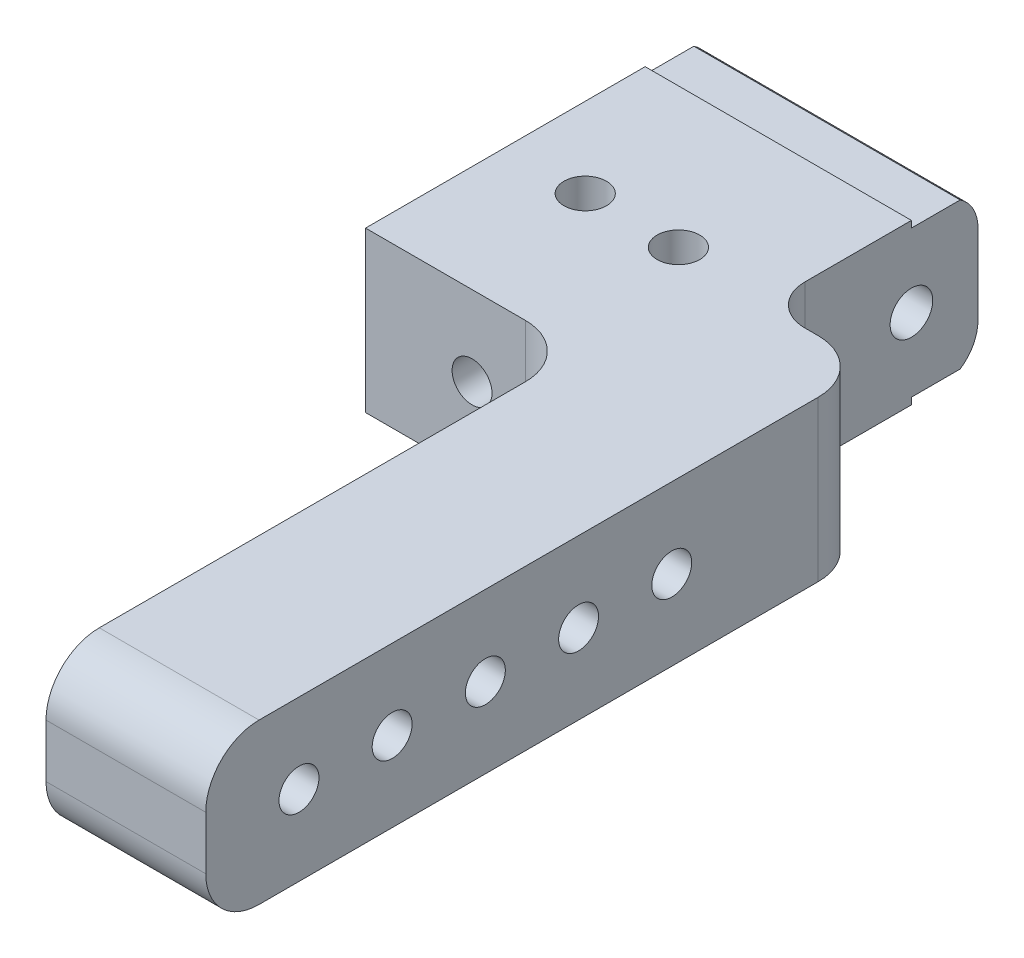
SolidWorks part; units mm, degrees
ref_plane "Front" through (0, 0, 0) normal (0, 0, 1) x (1, 0, 0)
ref_plane "Top" through (0, 0, 0) normal (0, 1, 0) x (1, 0, 0)
ref_plane "Right" through (0, 0, 0) normal (1, 0, 0) x (0, 0, -1)
sketch "Sketch1" plane through (0, 0, 0) normal (0, 0, 1) x (1, 0, 0)
  line L1 (0, 0) -> (20, 0)
  line L2 (0, 0) -> (0, -12)
  line L3 (0, -12) -> (20, -12)
  line L4 (20, 0) -> (20, -12)
  dimension "D1" = 20
  dimension "D2" = 12
extrude "Boss-Extrude1" add sketch "Sketch1" along normal blind 26
sketch "Sketch2" plane through (20, 0, 0) normal (1, 0, 0) x (0, 0, -1)
  line L0 (-26, 0) -> (0, 0) construction
  line L1 (-26, -12) -> (-16, -12)
  line L2 (-26, -12) -> (-26, 0)
  line L3 (-26, 0) -> (-16, 0)
  line L4 (-16, -12) -> (-16, 0)
  dimension "D1" = 10
extrude "Boss-Extrude2" add sketch "Sketch2" along normal blind 8
sketch "Sketch4" plane through (0, 0, 0) normal (0, 1, 0) x (1, 0, 0)
  line L0 (28, -26) -> (0, -26) construction
  line L1 (0, -26) -> (0, 0) construction
  circle A0 centre (13, -15.5) radius 1.6
  circle A1 centre (6, -15.5) radius 1.6
  dimension "D1" = 3.2
  dimension "D2" = 3.2
  dimension "D3" = 7
  dimension "D4" = 10.5
  dimension "D5" = 6
  dimension "D6" = 10.5
extrude "Cut-Extrude2" cut sketch "Sketch4" against normal through all
fillet "Fillet1" radius 3 1 edges at (20, -6, 16)
fillet "Fillet3" radius 3 2 edges at (10, -12, 0) (10, 0, 0)
sketch "Sketch5" plane through (0, 0, 0) normal (-1, 0, 0) x (0, 0, 1)
  line L0 (26, -12) -> (3, -12) construction
  line L1 (5, -12) -> (-4.9767, -12)
  line L2 (5, -12) -> (5, -11.5)
  line L3 (5, -11.5) -> (-4.9767, -11.5)
  line L4 (-4.9767, -12) -> (-4.9767, -11.5)
  line L5 (26, 0) -> (3, 0) construction
  line L6 (5, 0) -> (-7.2599, 0)
  line L7 (5, 0) -> (5, -0.5)
  line L8 (5, -0.5) -> (-7.2599, -0.5)
  line L9 (-7.2599, 0) -> (-7.2599, -0.5)
  line L10 (0, -3) -> (0, -9) construction
  dimension "D1" = 0.5
  dimension "D2" = 0.5
  dimension "D3" = 5
  dimension "D4" = 5
extrude "Cut-Extrude3" cut sketch "Sketch5" against normal through all
sketch "Sketch6" plane through (0, 0, 0) normal (0, 0, -1) x (-1, 0, 0)
  line L1 (-12.75, 7.3758) -> (-7.25, 7.3758)
  line L2 (-12.75, 7.3758) -> (-12.75, -23.1123)
  line L3 (-12.75, -23.1123) -> (-7.25, -23.1123)
  line L4 (-7.25, 7.3758) -> (-7.25, -23.1123)
  dimension "D1" = 5.5
  dimension "D2" = 7.25
extrude "Cut-Extrude4" cut sketch "Sketch6" against normal blind 0.8
sketch "Sketch8" plane through (0, 0, 26) normal (0, 0, 1) x (1, 0, 0)
  line L0 (28, 0) -> (0, 0) construction
  line L1 (28, -12) -> (16, -12)
  line L2 (28, -12) -> (28, 0)
  line L3 (28, 0) -> (16, 0)
  line L4 (16, -12) -> (16, 0)
  dimension "D1" = 12
extrude "Boss-Extrude3" add sketch "Sketch8" along normal blind 40
sketch "Sketch3" plane through (0, 0, 0) normal (-1, 0, 0) x (0, 0, 1)
  line L0 (0, -3) -> (0, -9) construction
  line L2 (26, -12) -> (5, -12) construction
  circle A0 centre (5, -6) radius 1.6
  dimension "D1" = 3.2
  dimension "D2" = 5
  dimension "D6" = 6
extrude "Cut-Extrude1" cut sketch "Sketch3" against normal through all
sketch "Sketch9" plane through (28, 0, 0) normal (1, 0, 0) x (0, 0, -1)
  line L0 (-16, -12) -> (-16, 0) construction
  circle A0 centre (-31, -6) radius 1.5
  circle A1 centre (-38, -6) radius 1.5
  circle A2 centre (-45, -6) radius 1.5
  circle A3 centre (-52, -6) radius 1.5
  circle A4 centre (-59, -6) radius 1.5
  dimension "D1" = 3
  dimension "D2" = 15
  dimension "D3" = 5
extrude "Cut-Extrude6" cut sketch "Sketch9" against normal blind 12
fillet "Fillet4" radius 4 1 edges at (16, -6, 26)
sketch "Sketch10" plane through (0, 0, 26) normal (0, 0, 1) x (1, 0, 0)
  line L0 (0, 0) -> (0, -12) construction
  circle A0 centre (8, -6) radius 1.5
  dimension "D1" = 3
  dimension "D2" = 8
extrude "Cut-Extrude7" cut sketch "Sketch10" against normal blind 12
fillet "Fillet5" radius 4 1 edges at (28, -6, 16)
fillet "Fillet7" radius 4 2 edges at (22, -12, 66) (22, 0, 66)
